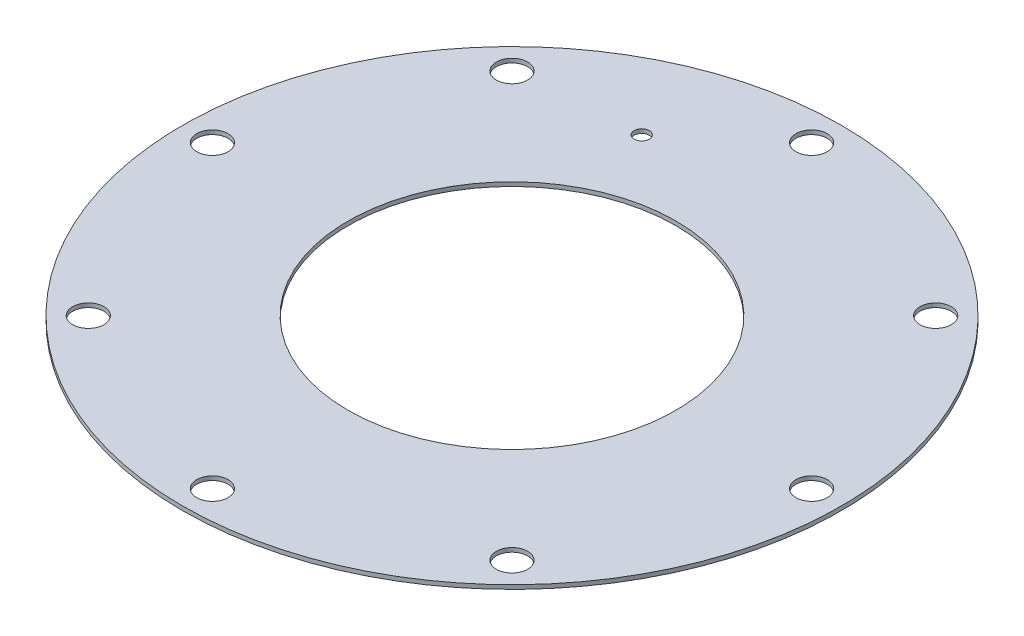
SolidWorks part; units mm, degrees
ref_plane "Front Plane" through (0, 0, 0) normal (0, 0, 1) x (1, 0, 0)
ref_plane "Top Plane" through (0, 0, 0) normal (0, 1, 0) x (1, 0, 0)
ref_plane "Right Plane" through (0, 0, 0) normal (1, 0, 0) x (0, 0, -1)
sketch "Sketch1" plane through (0, 0, 0) normal (0, 1, 0) x (1, 0, 0)
  circle A0 centre (0, 0) radius 69.85
  circle A1 centre (0, 0) radius 34.7526
  circle A2 centre (0, 63.5) radius 3.3147
  circle A3 centre (44.9013, 44.9013) radius 3.3147
  circle A4 centre (63.5, 0) radius 3.3147
  circle A5 centre (44.9013, -44.9013) radius 3.3147
  circle A6 centre (0, -63.5) radius 3.3147
  circle A7 centre (-44.9013, -44.9013) radius 3.3147
  circle A8 centre (-63.5, 0) radius 3.3147
  circle A9 centre (-44.9013, 44.9013) radius 3.3147
  circle A10 centre (-19.4403, 46.9331) radius 1.5875
  point P22 (0, 0)
  dimension "D1" = 6.6294
  dimension "D2" = 69.5052
  dimension "D3" = 139.7
  dimension "D4" = 63.5
  dimension "D6" = 3.175
  dimension "D7" = 22.5
  dimension "D8" = 50.8
  dimension "D5" = 8
extrude "Boss-Extrude1" add sketch "Sketch1" along normal blind 0.8636
